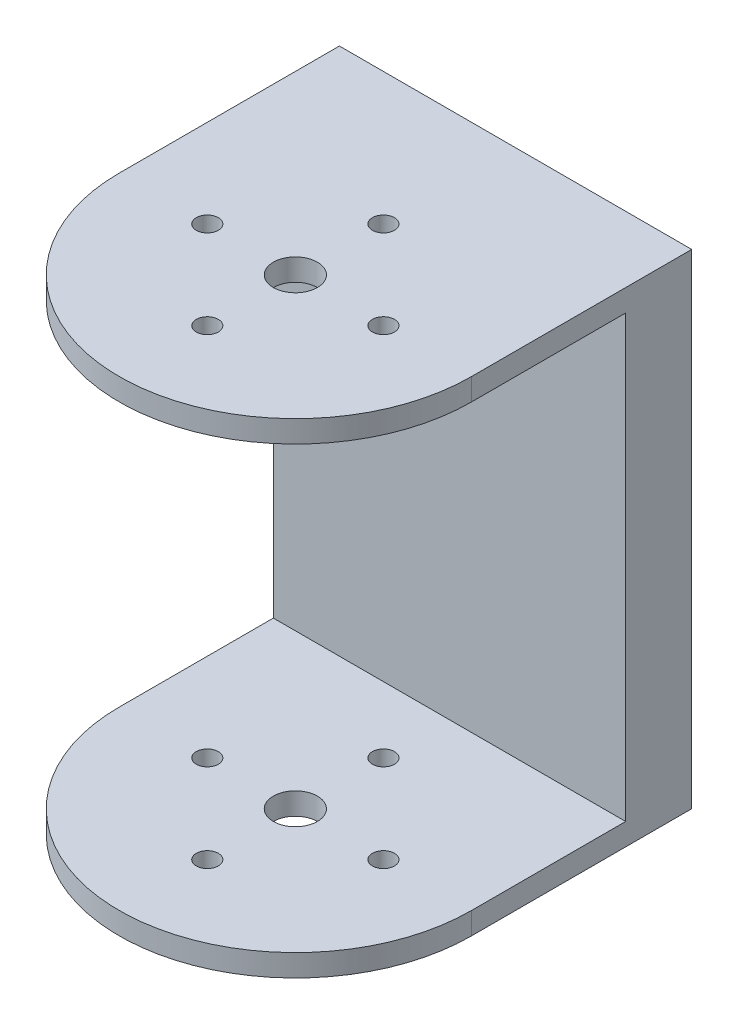
SolidWorks part; units mm, degrees
ref_plane "Front Plane" through (0, 0, 0) normal (0, 0, 1) x (1, 0, 0)
ref_plane "Top Plane" through (0, 0, 0) normal (0, 1, 0) x (1, 0, 0)
ref_plane "Right Plane" through (0, 0, 0) normal (1, 0, 0) x (0, 0, -1)
sketch "Sketch1" plane through (0, 0, 0) normal (0, 1, 0) x (1, 0, 0)
  line L0 (0, 0) -> (0, 8) construction
  line L1 (-16, 0) -> (-16, 20)
  line L2 (-16, 20) -> (16, 20)
  line L3 (16, 20) -> (16, 0)
  arc A0 (-16, 0) -> (16, 0) centre (0, 0) ccw
  circle A1 centre (0, 8) radius 1
  circle A2 centre (8, 0) radius 1
  circle A3 centre (0, -8) radius 1
  circle A4 centre (-8, 0) radius 1
  circle A5 centre (0, 0) radius 2
  dimension "D1" = 32
  dimension "D2" = 2
  dimension "D6" = 4
  dimension "D3" = 8
  dimension "D5" = 20
  dimension "D4" = 4
extrude "Boss-Extrude1" add sketch "Sketch1" along normal blind 44
sketch "Sketch2" plane through (16, 0, 0) normal (1, 0, 0) x (0, 0, -1)
  line L1 (-16, 42) -> (14, 42)
  line L2 (-16, 42) -> (-16, 2)
  line L3 (-16, 2) -> (14, 2)
  line L4 (14, 42) -> (14, 2)
  line L5 (-16, 42) -> (14, 2) construction
  line L6 (-16, 2) -> (14, 42) construction
  line L7 (0, 0) -> (20, 0) construction
  line L8 (-16, 44) -> (-16, 0) construction
  point P0 (-1, 22)
  dimension "D1" = 30
  dimension "D2" = 22
  dimension "D3" = 40
extrude "Cut-Extrude1" cut sketch "Sketch2" against normal through all
